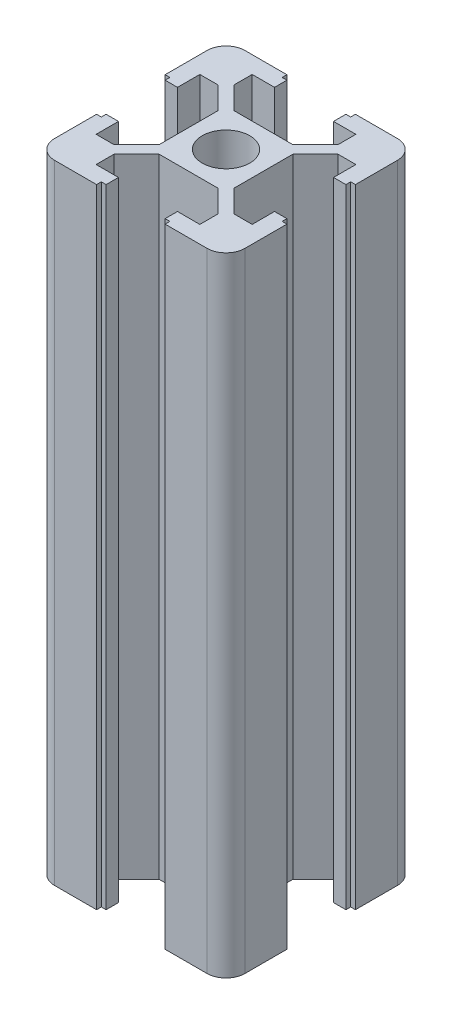
SolidWorks part; units mm, degrees
ref_plane "前视基准面" through (0, 0, 0) normal (0, 0, 1) x (1, 0, 0)
ref_plane "上视基准面" through (0, 0, 0) normal (0, 1, 0) x (1, 0, 0)
ref_plane "右视基准面" through (0, 0, 0) normal (1, 0, 0) x (0, 0, -1)
sketch "草图1" plane through (0, 0, 0) normal (0, 1, 0) x (1, 0, 0)
  line L0 (-6.2985, -5.45) -> (-3.9485, -3.1)
  line L1 (-5.45, -6.2985) -> (-3.1, -3.9485)
  line L2 (-6.2985, -5.45) -> (-8.2, -5.45)
  line L3 (-8.2, -5.45) -> (-8.2, -3.1)
  line L4 (-8.2, -3.1) -> (-10, -3.1)
  line L5 (-10, -3.1) -> (-10, -8)
  line L6 (-8, -10) -> (-3.1, -10)
  line L7 (-5.45, -6.2985) -> (-5.45, -8.2)
  line L8 (-5.45, -8.2) -> (-3.1, -8.2)
  line L9 (-3.1, -8.2) -> (-3.1, -10)
  line L10 (-3.9485, 0) -> (-3.9485, -3.1)
  line L11 (-3.1, -3.9485) -> (0, -3.9485)
  line L12 (-10, -3.6) -> (-9.5, -3.6)
  line L13 (-9.5, -3.6) -> (-9.5, -3.1)
  line L14 (-3.6, -10) -> (-3.6, -9.5)
  line L15 (-3.6, -9.5) -> (-3.1, -9.5)
  line L16 (-3.9485, 0) -> (-2.5, 0) construction
  line L17 (0, -2.5) -> (0, -3.9485) construction
  line L18 (-5.45, 6.2985) -> (-3.1, 3.9485)
  line L19 (-6.2985, 5.45) -> (-3.9485, 3.1)
  line L20 (-5.45, 6.2985) -> (-5.45, 8.2)
  line L21 (-5.45, 8.2) -> (-3.1, 8.2)
  line L22 (-3.1, 8.2) -> (-3.1, 10)
  line L23 (-3.1, 10) -> (-8, 10)
  line L24 (-10, 8) -> (-10, 3.1)
  line L25 (-6.2985, 5.45) -> (-8.2, 5.45)
  line L26 (-8.2, 5.45) -> (-8.2, 3.1)
  line L27 (-8.2, 3.1) -> (-10, 3.1)
  line L28 (-3.1, 3.9485) -> (0, 3.9485)
  line L29 (-3.9485, 3.1) -> (-3.9485, 0)
  line L30 (-3.6, 10) -> (-3.6, 9.5)
  line L31 (-3.6, 9.5) -> (-3.1, 9.5)
  line L32 (-10, 3.6) -> (-9.5, 3.6)
  line L33 (-9.5, 3.6) -> (-9.5, 3.1)
  line L34 (0, 3.9485) -> (0, 2.5) construction
  line L35 (-2.5, 0) -> (-3.9485, 0) construction
  line L36 (6.2985, 5.45) -> (3.9485, 3.1)
  line L37 (5.45, 6.2985) -> (3.1, 3.9485)
  line L38 (6.2985, 5.45) -> (8.2, 5.45)
  line L39 (8.2, 5.45) -> (8.2, 3.1)
  line L40 (8.2, 3.1) -> (10, 3.1)
  line L41 (10, 3.1) -> (10, 8)
  line L42 (8, 10) -> (3.1, 10)
  line L43 (5.45, 6.2985) -> (5.45, 8.2)
  line L44 (5.45, 8.2) -> (3.1, 8.2)
  line L45 (3.1, 8.2) -> (3.1, 10)
  line L46 (3.9485, 0) -> (3.9485, 3.1)
  line L47 (3.1, 3.9485) -> (0, 3.9485)
  line L48 (10, 3.6) -> (9.5, 3.6)
  line L49 (9.5, 3.6) -> (9.5, 3.1)
  line L50 (3.6, 10) -> (3.6, 9.5)
  line L51 (3.6, 9.5) -> (3.1, 9.5)
  line L52 (3.9485, 0) -> (2.5, 0) construction
  line L53 (0, 2.5) -> (0, 3.9485) construction
  line L54 (5.45, -6.2985) -> (3.1, -3.9485)
  line L55 (6.2985, -5.45) -> (3.9485, -3.1)
  line L56 (5.45, -6.2985) -> (5.45, -8.2)
  line L57 (5.45, -8.2) -> (3.1, -8.2)
  line L58 (3.1, -8.2) -> (3.1, -10)
  line L59 (3.1, -10) -> (8, -10)
  line L60 (10, -8) -> (10, -3.1)
  line L61 (6.2985, -5.45) -> (8.2, -5.45)
  line L62 (8.2, -5.45) -> (8.2, -3.1)
  line L63 (8.2, -3.1) -> (10, -3.1)
  line L64 (0, -3.9485) -> (3.1, -3.9485)
  line L65 (3.9485, -3.1) -> (3.9485, 0)
  line L66 (3.6, -10) -> (3.6, -9.5)
  line L67 (3.6, -9.5) -> (3.1, -9.5)
  line L68 (10, -3.6) -> (9.5, -3.6)
  line L69 (9.5, -3.6) -> (9.5, -3.1)
  line L70 (0, -3.9485) -> (0, -2.5) construction
  line L71 (2.5, 0) -> (3.9485, 0) construction
  line L72 (0, 3.9485) -> (-3.1, 3.9485) [skipped]
  circle A0 centre (0, 0) radius 2.5
  arc A1 (-10, -8) -> (-8, -10) centre (-8, -8) ccw
  arc A3 (-8, 10) -> (-10, 8) centre (-8, 8) ccw
  arc A5 (10, 8) -> (8, 10) centre (8, 8) ccw
  arc A7 (8, -10) -> (10, -8) centre (8, -8) ccw
  point P25 (-10, -10)
  point P98 (0, 0)
  dimension "D9" = 2
  dimension "D15" = 5
  dimension "D2" = 1.2
  dimension "D4" = 5.45
  dimension "D5" = 1.8
  dimension "D6" = 3.1
  dimension "D7" = 135
  dimension "D10" = 0.5
  dimension "D11" = 0.5
  dimension "D12" = 0.5
  dimension "D13" = 0.5
  dimension "D14" = 4
extrude "凸台-拉伸1" add sketch "草图1" along normal blind 66 contours L59 A7 L60 L68 L69 L63 L62 L61 L55 L65 L46 L36 L38 L39 L40 L49 L48 L41 A5 L42 L50 L51 L45 L44 L43 L37 L47 L28 L18 L20 L21 L22 L31 L30 L23 A3 L24 L32 L33 L27 L26 L25 L19 L29 L10 L0 L2 L3 L4 L13 L12
